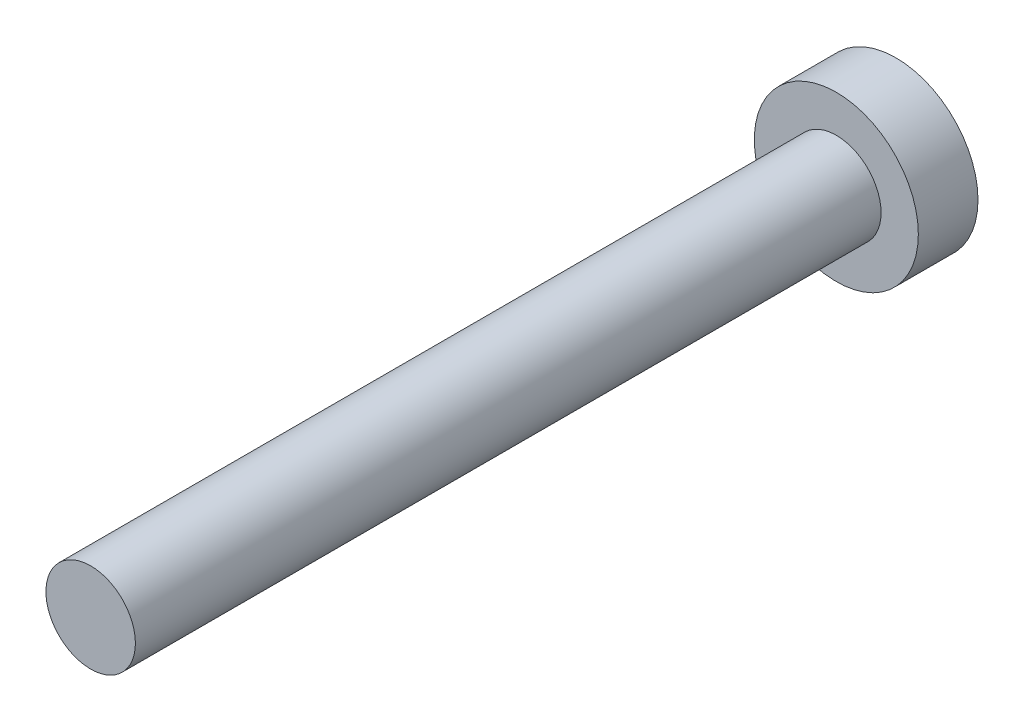
SolidWorks part; units mm, degrees
ref_plane "Plan de face" through (0, 0, 0) normal (0, 0, 1) x (1, 0, 0)
ref_plane "Plan de dessus" through (0, 0, 0) normal (0, 1, 0) x (1, 0, 0)
ref_plane "Plan de droite" through (0, 0, 0) normal (1, 0, 0) x (0, 0, -1)
sketch "Esquisse1" plane through (0, 0, 0) normal (0, 0, 1) x (1, 0, 0)
  circle A0 centre (0, 0) radius 2.75
  dimension "D1" = 5.5
extrude "Boss.-Extru.1" add sketch "Esquisse1" along normal blind 2
sketch "Esquisse2" plane through (0, 0, 2) normal (0, 0, 1) x (1, 0, 0)
  circle A0 centre (0, 0) radius 1.5
extrude "Boss.-Extru.2" add sketch "Esquisse2" along normal blind 25
